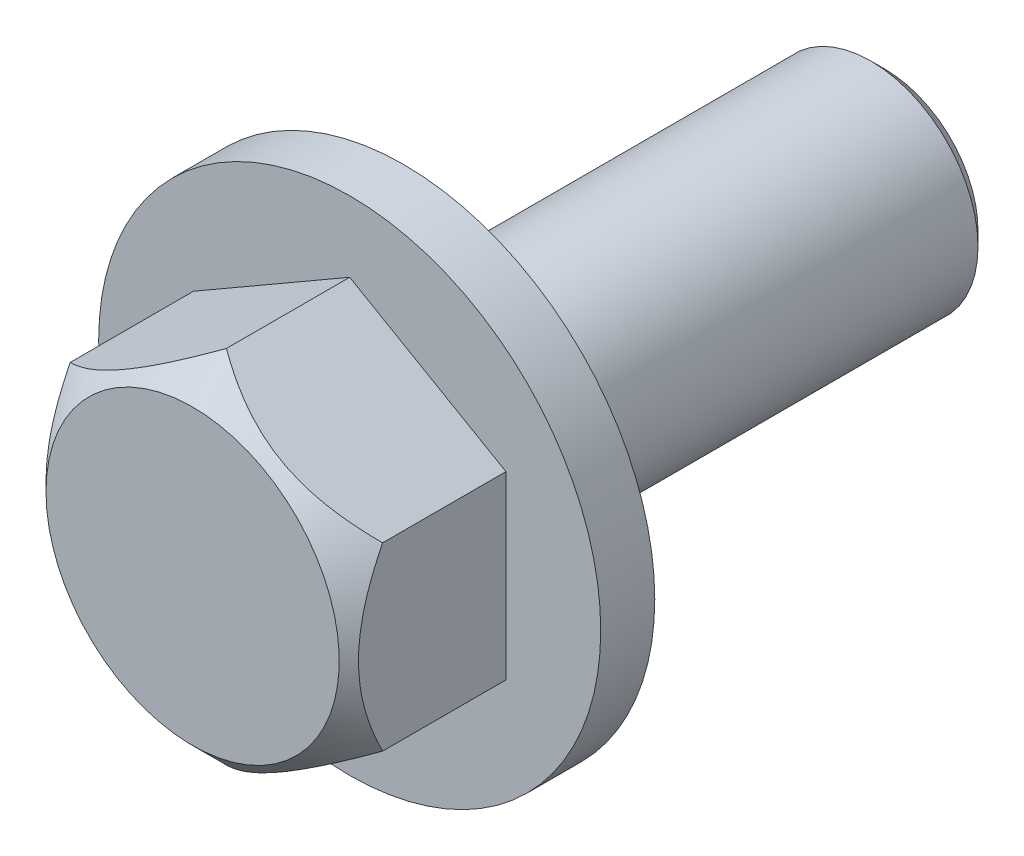
SolidWorks part; units mm, degrees
ref_plane "Front Plane" through (0, 0, 0) normal (0, 0, 1) x (1, 0, 0)
ref_plane "Top Plane" through (0, 0, 0) normal (0, 1, 0) x (1, 0, 0)
ref_plane "Right Plane" through (0, 0, 0) normal (1, 0, 0) x (0, 0, -1)
sketch "Sketch6" plane through (0, 0, 0) normal (0, 0, 1) x (1, 0, 0)
  line L1 (0, 10.681) -> (-9.25, 5.3405)
  line L2 (-9.25, 5.3405) -> (-9.25, -5.3405)
  line L3 (-9.25, -5.3405) -> (0, -10.681)
  line L4 (0, -10.681) -> (9.25, -5.3405)
  line L5 (9.25, -5.3405) -> (9.25, 5.3405)
  line L6 (9.25, 5.3405) -> (0, 10.681)
  circle A0 centre (0, 0) radius 9.25 construction
  point P1 (0, 0)
  dimension "D1" = 18.5
extrude "Boss-Extrude2" add sketch "Sketch6" along normal blind 9.3
sketch "Sketch8" plane through (0, 0, 0) normal (1, 0, 0) x (0, 0, -1)
  line L0 (-7.3, 10.681) -> (-9.3, 8.681)
  line L1 (-9.3, 10.681) -> (0, 10.681) construction
  line L2 (-9.3, 5.3405) -> (-9.3, 10.681) construction
  line L3 (0, 0) -> (-12.5114, 0) construction
  line L4 (-9.3, 8.681) -> (-9.3, 10.681)
  line L5 (-9.3, 10.681) -> (-7.3, 10.681)
  dimension "D1" = 2
  dimension "D2" = 2
revolve "Cut-Revolve1" cut sketch "Sketch8" angle 360 about L3
sketch "Sketch10" plane through (0, 0, 0) normal (1, 0, 0) x (0, 0, -1)
  line L0 (0, 0) -> (0, 14.8637)
  line L1 (0, 14.8637) -> (3.2, 14.8637)
  line L2 (3.2, 14.8637) -> (3.2, 6.35)
  line L3 (3.2, 6.35) -> (30.8515, 6.35)
  line L4 (31.7, 5.5015) -> (31.7, 0)
  line L5 (31.7, 0) -> (0, 0)
  line L6 (30.8515, 6.35) -> (31.7, 5.5015)
  line L7 (-9.3, 8.681) -> (-9.3, -8.681) construction
  dimension "D1" = 3.2
  dimension "D2" = 41
  dimension "D3" = 1.2
  dimension "D4" = 6.35
revolve "Revolve1" add sketch "Sketch10" angle 360 about L5
